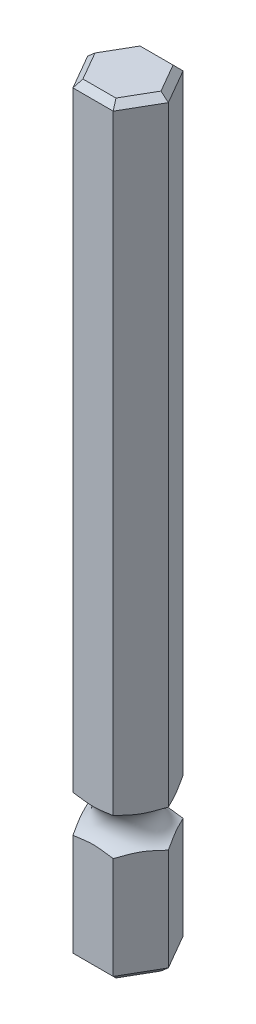
SolidWorks part; units mm, degrees
ref_plane "Front Plane" through (0, 0, 0) normal (0, 0, 1) x (1, 0, 0)
ref_plane "Top Plane" through (0, 0, 0) normal (0, 1, 0) x (1, 0, 0)
ref_plane "Right Plane" through (0, 0, 0) normal (1, 0, 0) x (0, 0, -1)
sketch "Sketch2" plane through (0, 0, 0) normal (0, 0, 1) x (1, 0, 0)
  line L0 (-1.75, -18.5) -> (-1.75, 30)
  line L1 (-1.75, -30) -> (1.75, -30)
  line L2 (-1.75, -30) -> (-1.75, -21.5)
  line L3 (-1.75, 30) -> (1.75, 30)
  line L4 (1.75, -30) -> (1.75, 30)
  line L5 (-1.75, -30) -> (1.75, 30) construction
  line L6 (-1.75, 30) -> (1.75, -30) construction
  arc A0 (-1.75, -21.5) -> (-1.75, -18.5) centre (-1.75, -20) ccw
  point P0 (0, 0)
  dimension "D4" = 3
  dimension "D1" = 60
  dimension "D2" = 3.5
sketch "Sketch3" plane through (0, 0, 0) normal (0, 0, 1) x (1, 0, 0)
  circle A0 centre (-1.75, -20) radius 1.7659
  dimension "D1" = 3.5317
revolve "Revolve1" add sketch "Sketch2" angle 360 about L4
sketch "Sketch5" plane through (0, 0, 0) normal (0, 1, 0) x (1, 0, 0)
  line L1 (4.925, 0) -> (3.3375, 2.7496)
  line L2 (3.3375, 2.7496) -> (0.1625, 2.7496)
  line L3 (0.1625, 2.7496) -> (-1.425, 0)
  line L4 (-1.425, 0) -> (0.1625, -2.7496)
  line L5 (0.1625, -2.7496) -> (3.3375, -2.7496)
  line L6 (3.3375, -2.7496) -> (4.925, 0)
  circle A0 centre (1.75, 0) radius 4
  circle A1 centre (1.75, 0) radius 2.7496 construction
  dimension "D1" = 8
extrude "Cut-Extrude1" cut sketch "Sketch5" against normal through all both and the other way through all
chamfer "Chamfer1" distance 0.5 angle 45 12 edges at (4.1312, -30, -1.3748) (1.75, -30, -2.7496) (-0.6313, -30, -1.3748) (-0.6312, -30, 1.3748) (1.75, -30, 2.7496) (4.1313, -30, 1.3748) (1.75, 30, 2.7496) (-0.6312, 30, 1.3748) (-0.6313, 30, -1.3748) (1.75, 30, -2.7496) (4.1312, 30, -1.3748) (4.1313, 30, 1.3748)
